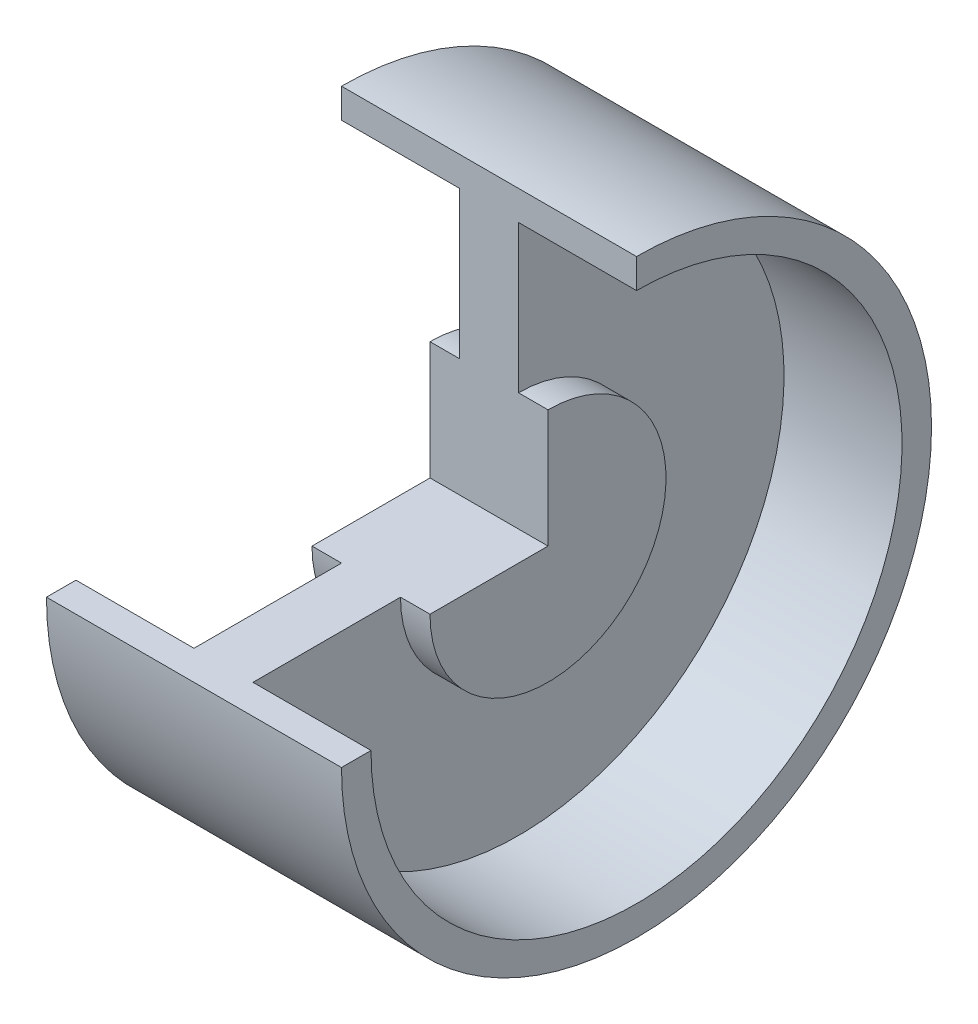
SolidWorks part; units mm, degrees
ref_plane "Front Plane" through (0, 0, 0) normal (0, 0, 1) x (1, 0, 0)
ref_plane "Top Plane" through (0, 0, 0) normal (0, 1, 0) x (1, 0, 0)
ref_plane "Right Plane" through (0, 0, 0) normal (1, 0, 0) x (0, 0, -1)
sketch "Sketch3" plane through (0, 0, 0) normal (0, 0, 1) x (1, 0, 0)
  line L0 (10, 0) -> (-10, 0)
  line L1 (-10, 0) -> (-10, 20)
  line L2 (-10, 20) -> (-5, 20)
  line L3 (-5, 20) -> (-5, 45)
  line L4 (-5, 45) -> (-25, 45)
  line L5 (-25, 45) -> (-25, 50)
  line L6 (-25, 50) -> (-5, 50)
  line L7 (-5, 50) -> (5, 50)
  line L8 (0, 50) -> (0, -2.9063) construction
  line L9 (10, 20) -> (5, 20)
  line L10 (10, 0) -> (10, 20)
  line L11 (5, 20) -> (5, 45)
  line L12 (5, 45) -> (25, 45)
  line L13 (25, 45) -> (25, 50)
  line L14 (25, 50) -> (5, 50)
  point P12 (0, 0)
revolve "Revolve1" add sketch "Sketch3" angle 270 about L0
